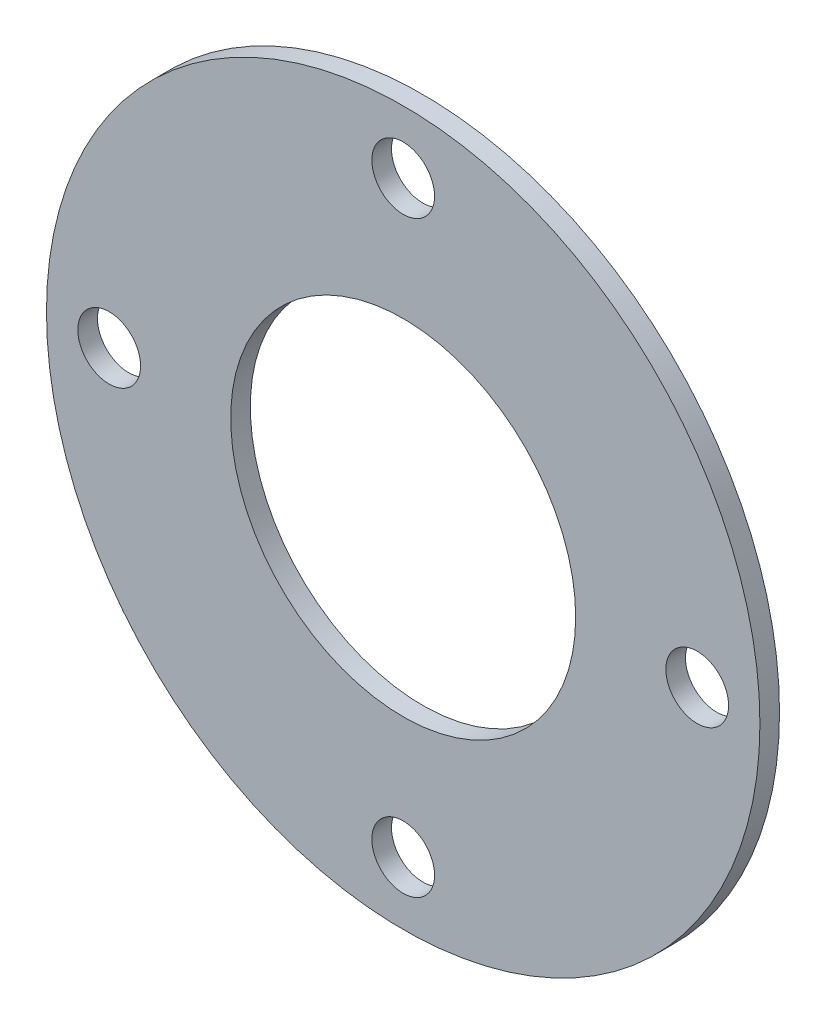
SolidWorks part; units mm, degrees
ref_plane "Спереди" through (0, 0, 0) normal (0, 0, 1) x (1, 0, 0)
ref_plane "Сверху" through (0, 0, 0) normal (0, 1, 0) x (1, 0, 0)
ref_plane "Справа" through (0, 0, 0) normal (1, 0, 0) x (0, 0, -1)
sketch "Эскиз1" plane through (0, 0, 0) normal (0, 0, 1) x (1, 0, 0)
  circle A0 centre (0, 0) radius 45.5
  circle A1 centre (0, 0) radius 22
extrude "Carrier_rear" add sketch "Эскиз1" along normal blind 2.5 from offset 32
sketch "Эскиз2" plane through (0, 0, 0) normal (0, 0, 1) x (1, 0, 0)
  circle A0 centre (37.5, 0) radius 4
  circle A1 centre (0, 37.5) radius 4
  circle A2 centre (-37.5, 0) radius 4
  circle A3 centre (0, -37.5) radius 4
extrude "Through_holes" cut sketch "Эскиз2" against normal mid plane 200
